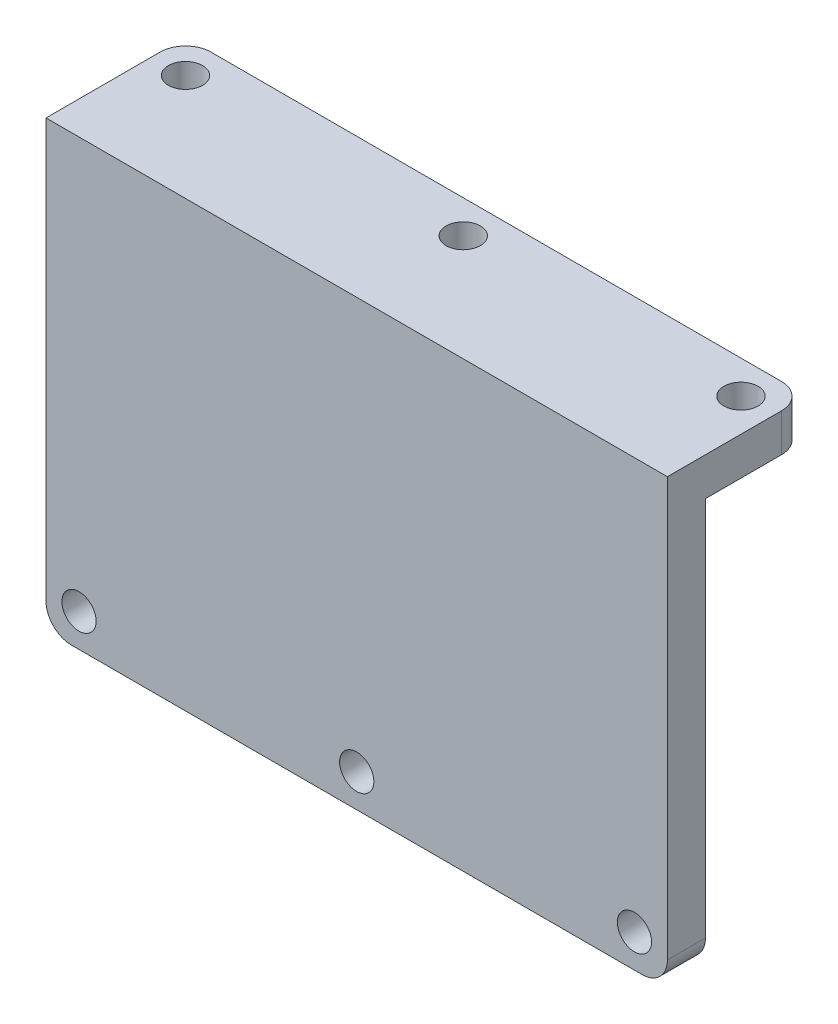
SolidWorks part; units mm, degrees
ref_plane "Plano frontal" through (0, 0, 0) normal (0, 0, 1) x (1, 0, 0)
ref_plane "Plano superior" through (0, 0, 0) normal (0, 1, 0) x (1, 0, 0)
ref_plane "Plano direito" through (0, 0, 0) normal (1, 0, 0) x (0, 0, -1)
sketch "Esboço1" plane through (0, 0, 0) normal (0, 0, 1) x (1, 0, 0)
  line L1 (-24.5, 17.5) -> (24.5, 17.5)
  line L2 (-24.5, 17.5) -> (-24.5, -17.5)
  line L3 (-24.5, -17.5) -> (24.5, -17.5)
  line L4 (24.5, 17.5) -> (24.5, -17.5)
  line L5 (-24.5, 17.5) -> (24.5, -17.5) construction
  line L6 (-24.5, -17.5) -> (24.5, 17.5) construction
  point P0 (0, 0)
  dimension "D1" = 49
  dimension "D2" = 35
extrude "Ressalto-extrusão1" add sketch "Esboço1" along normal blind 3
sketch "Esboço2" plane through (0, 0, 0) normal (0, 0, -1) x (-1, 0, 0)
  line L0 (-24.5, -17.5) -> (-24.5, 17.5) construction
  line L1 (24.5, -17.5) -> (-24.5, -17.5) construction
  line L2 (24.5, 17.5) -> (24.5, -17.5) construction
  circle A0 centre (-21.9, -14.9) radius 1.35
  circle A1 centre (0, -14.9) radius 1.35
  circle A2 centre (21.9, -14.9) radius 1.35
  dimension "D1" = 2.7
  dimension "D2" = 2.6
  dimension "D5" = 2.6
  dimension "D3" = 2.6
  dimension "D4" = 24.5
  dimension "D6" = 2.6
  dimension "D7" = 2.6
extrude "Corte-extrusão1" cut sketch "Esboço2" against normal through all
sketch "Esboço3" plane through (0, 0, 0) normal (0, 0, -1) x (-1, 0, 0)
  line L0 (24.5, 17.5) -> (24.5, -17.5) construction
  line L1 (-24.5, 17.5) -> (24.5, 17.5)
  line L2 (-24.5, 17.5) -> (-24.5, 14.5)
  line L3 (-24.5, 14.5) -> (24.5, 14.5)
  line L4 (24.5, 17.5) -> (24.5, 14.5)
  dimension "D1" = 3
extrude "Ressalto-extrusão3" add sketch "Esboço3" along normal blind 8
sketch "Esboço4" plane through (0, 17.5, 0) normal (0, 1, 0) x (1, 0, 0)
  line L0 (-24.5, -3) -> (-24.5, 8) construction
  line L1 (-24.5, 8) -> (24.5, 8) construction
  line L2 (24.5, -3) -> (24.5, 8) construction
  circle A0 centre (-21.9, 5.4) radius 1.35
  circle A1 centre (0, 5.4) radius 1.35
  circle A2 centre (21.9, 5.4) radius 1.35
  dimension "D1" = 2.7
  dimension "D2" = 2.6
  dimension "D3" = 2.6
  dimension "D4" = 2.6
  dimension "D5" = 2.6
  dimension "D6" = 2.6
  dimension "D7" = 24.5
extrude "Corte-extrusão2" cut sketch "Esboço4" against normal through all
fillet "Filete1" radius 2 2 edges at (24.5, -17.5, 1.5) (-24.5, -17.5, 1.5)
fillet "Filete2" radius 2 2 edges at (-24.5, 16, -8) (24.5, 16, -8)
